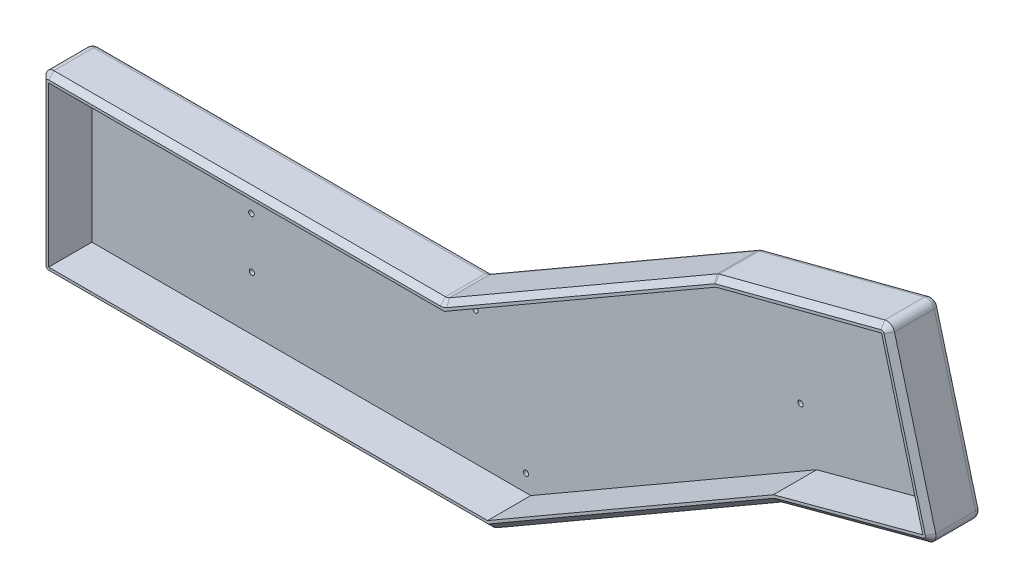
SolidWorks part; units mm, degrees
ref_plane "Plan de face" through (0, 0, 0) normal (0, 0, 1) x (1, 0, 0)
ref_plane "Plan de dessus" through (0, 0, 0) normal (0, 1, 0) x (1, 0, 0)
ref_plane "Plan de droite" through (0, 0, 0) normal (1, 0, 0) x (0, 0, -1)
sketch "Model" plane through (0, 0, 0) normal (0, 0, 1) x (1, 0, 0)
  line L0 (152.8114, 25.9717) -> (138.2826, 80.2215) construction
  line L1 (98.1506, 11.3316) -> (152.8114, 25.9717) construction
  line L2 (-9.3986, -50.8585) -> (98.1506, 11.3316) construction
  line L3 (-172.3739, -50.8585) -> (-9.3986, -50.8585) construction
  line L4 (-24.5886, 5.3017) -> (-172.3739, 5.2915) construction
  line L5 (138.2826, 80.2215) -> (78.0109, 64.5416) construction
  line L6 (-151.6088, 5.3124) -> (-151.6088, 5.2929)
  line L7 (-24.5886, 5.3017) -> (78.0109, 64.5416) construction
  line L8 (-172.3739, 5.2915) -> (-172.3739, -50.6876) construction
  line L9 (-172.3739, -50.6876) -> (-172.3739, -50.8585) construction
  line L10 (-25.1245, 7.3016) -> (-174.3739, 7.2914)
  line L11 (-174.3739, 7.2914) -> (-174.3739, -50.6876)
  line L12 (-174.3739, -50.6876) -> (-174.3739, -52.8585)
  line L13 (-174.3739, -52.8585) -> (-8.862, -52.8585)
  line L14 (-8.862, -52.8585) -> (98.9231, 9.4681)
  line L15 (98.9231, 9.4681) -> (155.2607, 24.5572)
  line L16 (155.2607, 24.5572) -> (139.7008, 82.657)
  line L17 (139.7008, 82.657) -> (77.2454, 66.409)
  line L18 (-25.1245, 7.3016) -> (77.2454, 66.409)
  line L19 (-25.9285, 10.3016) -> (-177.3739, 10.2912)
  line L20 (-177.3739, 10.2912) -> (-177.3739, -50.6876)
  line L21 (-177.3739, -50.6876) -> (-177.3739, -55.8585)
  line L22 (-177.3739, -55.8585) -> (-8.057, -55.8585)
  line L23 (-8.057, -55.8585) -> (100.0819, 6.6727)
  line L24 (100.0819, 6.6727) -> (158.9346, 22.4355)
  line L25 (158.9346, 22.4355) -> (141.8281, 86.3103)
  line L26 (141.8281, 86.3103) -> (76.097, 69.2101)
  line L27 (-25.9285, 10.3016) -> (76.097, 69.2101)
  circle A0 centre (80.6856, 58.4893) radius 1
  circle A1 centre (92.8776, 28.0855) radius 1
  circle A2 centre (-29.7028, -2.6485) radius 1
  circle A3 centre (-10.6528, -46.4381) radius 1
  circle A4 centre (-114.2594, -13.4181) radius 1
  circle A5 centre (-114.0308, -32.4935) radius 1
  point P24 (0, 0)
  dimension "D1" = 2
  dimension "D2" = 3
extrude "Boss.-Extru.1" add sketch "Model" along normal blind 19 contours L27 L19 L20 L21 L22 L23 L24 L25 L26 L10 L18 L17 L16 L15 L14 L13 L12 L11
fillet "Congé1" radius 3 8 edges at (-25.9285, 10.3016, 9.5) (76.097, 69.2101, 9.5) (141.8281, 86.3103, 9.5) (158.9346, 22.4355, 9.5) (100.0819, 6.6727, 9.5) (-8.057, -55.8585, 9.5) (-177.3739, -55.8585, 9.5) (-177.3739, 10.2912, 9.5)
sketch "Esquisse1" plane through (0, 0, 0) normal (0, 0, 1) x (1, 0, 0)
  line L0 (-25.1245, 7.3016) -> (-174.3739, 7.2914) construction
  line L1 (-25.1245, 7.3016) -> (77.2454, 66.409) construction
  line L2 (139.7008, 82.657) -> (77.2454, 66.409) construction
  line L3 (155.2607, 24.5572) -> (139.7008, 82.657) construction
  line L4 (98.9231, 9.4681) -> (155.2607, 24.5572) construction
  line L5 (-8.862, -52.8585) -> (98.9231, 9.4681) construction
  line L6 (-174.3739, -52.8585) -> (-8.862, -52.8585) construction
  line L7 (-174.3739, -50.6876) -> (-174.3739, -52.8585) construction
  line L8 (-174.3739, 7.2914) -> (-174.3739, -50.6876) construction
  line L9 (-25.1245, 7.3016) -> (-174.3739, 7.2914)
  line L10 (-25.1245, 7.3016) -> (77.2454, 66.409)
  line L11 (139.7008, 82.657) -> (77.2454, 66.409)
  line L12 (155.2607, 24.5572) -> (139.7008, 82.657)
  line L13 (98.9231, 9.4681) -> (155.2607, 24.5572)
  line L14 (-8.862, -52.8585) -> (98.9231, 9.4681)
  line L15 (-174.3739, -52.8585) -> (-8.862, -52.8585)
  line L16 (-174.3739, -50.6876) -> (-174.3739, -52.8585)
  line L17 (-174.3739, 7.2914) -> (-174.3739, -50.6876)
  circle A0 centre (-114.2594, -13.4181) radius 1 construction
  circle A1 centre (-114.2594, -13.4181) radius 1
  circle A2 centre (-114.0308, -32.4935) radius 1 construction
  circle A3 centre (-114.0308, -32.4935) radius 1
  circle A4 centre (-29.7028, -2.6485) radius 1 construction
  circle A5 centre (-29.7028, -2.6485) radius 1
  circle A6 centre (-10.6528, -46.4381) radius 1 construction
  circle A7 centre (-10.6528, -46.4381) radius 1
  circle A8 centre (80.6856, 58.4893) radius 1 construction
  circle A9 centre (80.6856, 58.4893) radius 1
  circle A10 centre (92.8776, 28.0855) radius 1 construction
  circle A11 centre (92.8776, 28.0855) radius 1
extrude "Boss.-Extru.2" add sketch "Esquisse1" along normal blind 2.7
sketch "Esquisse2" plane through (0, 0, 0) normal (0, 0, -1) x (-1, 0, 0)
  circle A0 centre (-80.6856, 58.4893) radius 1 construction
  circle A1 centre (-92.8776, 28.0855) radius 1 construction
  circle A2 centre (29.7028, -2.6485) radius 1 construction
  circle A3 centre (10.6528, -46.4381) radius 1 construction
  circle A4 centre (114.2594, -13.4181) radius 1 construction
  circle A5 centre (114.0308, -32.4935) radius 1 construction
  circle A6 centre (-80.6856, 58.4893) radius 1
  circle A7 centre (-92.8776, 28.0855) radius 1
  circle A8 centre (29.7028, -2.6485) radius 1
  circle A9 centre (10.6528, -46.4381) radius 1
  circle A10 centre (114.2594, -13.4181) radius 1
  circle A11 centre (114.0308, -32.4935) radius 1
  circle A12 centre (-80.6856, 58.4893) radius 2
  circle A13 centre (-92.8776, 28.0855) radius 2
  circle A14 centre (29.7028, -2.6485) radius 2
  circle A15 centre (10.6528, -46.4381) radius 2
  circle A16 centre (114.2594, -13.4181) radius 2
  circle A17 centre (114.0308, -32.4935) radius 2
  dimension "D1" = 1
extrude "Enlèv. mat.-Extru.1" cut sketch "Esquisse2" against normal blind 1
chamfer "Chanfrein1" distance 2 angle 45 16 edges at (141.2104, 85.2495, 19) (150.3786, 54.3832, 19) (157.8586, 23.0569, 19) (128.2507, 14.2173, 19) (100.0919, 6.6486, 19) (46.1894, -24.4906, 19) (-8.0845, -55.756, 19) (-91.6179, -55.8585, 19) (-176.4952, -54.9798, 19) (-177.3739, -22.7836, 19) (-176.4953, 9.4126, 19) (-100.5532, 10.2965, 19) (-25.9559, 10.4038, 19) (25.2564, 39.8553, 19) (76.1074, 69.1848, 19) (107.7178, 77.4364, 19)
fillet "Congé2" radius 2 16 edges at (100.0919, 6.6486, 0) (46.1894, -24.4906, 0) (-8.0845, -55.756, 0) (-91.6179, -55.8585, 0) (-176.4952, -54.9798, 0) (-177.3739, -22.7836, 0) (-176.4953, 9.4126, 0) (-100.5532, 10.2965, 0) (-25.9559, 10.4038, 0) (25.2564, 39.8553, 0) (76.1074, 69.1848, 0) (107.7178, 77.4364, 0) (141.2104, 85.2495, 0) (150.3786, 54.3832, 0) (157.8586, 23.0569, 0) (128.2507, 14.2173, 0)
